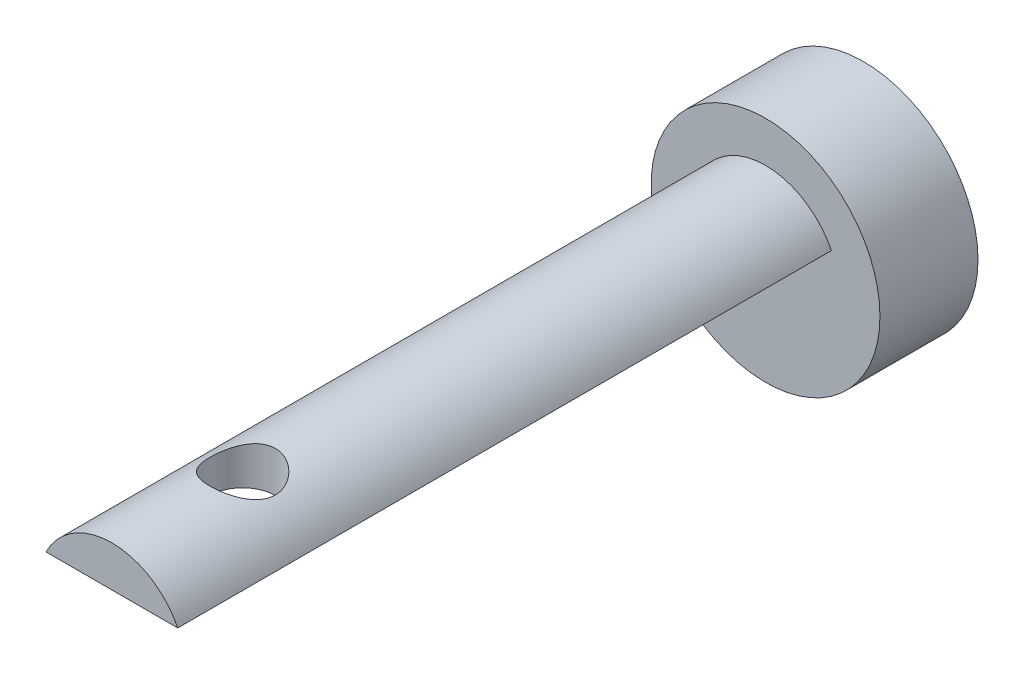
SolidWorks part; units mm, degrees
ref_plane "Front Plane" through (0, 0, 0) normal (0, 0, 1) x (1, 0, 0)
ref_plane "Top Plane" through (0, 0, 0) normal (0, 1, 0) x (1, 0, 0)
ref_plane "Right Plane" through (0, 0, 0) normal (1, 0, 0) x (0, 0, -1)
sketch "Sketch1" plane through (0, 0, 0) normal (0, 0, 1) x (1, 0, 0)
  line L0 (-3.4737, 1) -> (4.1684, 1)
  circle A0 centre (0, 0) radius 3.5
  dimension "D2" = 7
  dimension "D1" = 1
extrude "Boss-Extrude1" add sketch "Sketch1" along normal blind 3 contours L0 A0
sketch "Sketch2" plane through (0, 0, 3) normal (0, 0, 1) x (1, 0, 0)
  line L0 (-2.0156, 1) -> (2.0156, 1)
  circle A0 centre (0, 0) radius 2.25
  dimension "D1" = 4.5
  dimension "D2" = 1
extrude "Boss-Extrude2" add sketch "Sketch2" along normal blind 20
sketch "Sketch3" plane through (0, 1, 0) normal (0, -1, 0) x (-1, 0, 0)
  line L0 (2.0156, -23) -> (-2.0156, -23) construction
  line L1 (2.0156, -3) -> (-2.0156, -3) construction
  circle A0 centre (0, -19) radius 1
  point P4 (0, -23)
  dimension "D1" = 16
  dimension "D2" = 0
  dimension "D3" = 2
extrude "Cut-Extrude1" cut sketch "Sketch3" against normal blind 10
